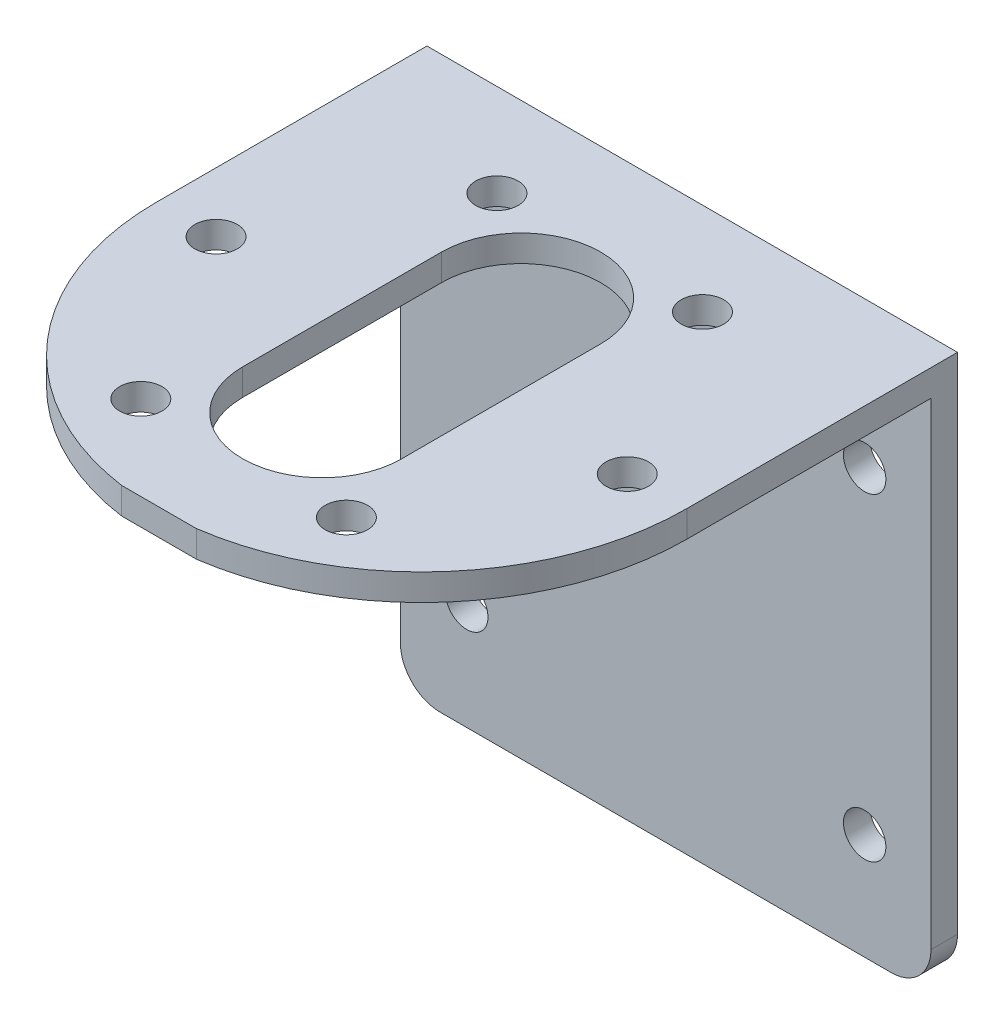
SolidWorks part; units mm, degrees
ref_plane "前视基准面" through (0, 0, 0) normal (0, 0, 1) x (1, 0, 0)
ref_plane "上视基准面" through (0, 0, 0) normal (0, 1, 0) x (1, 0, 0)
ref_plane "右视基准面" through (0, 0, 0) normal (1, 0, 0) x (0, 0, -1)
other "Configuration Table"
sketch "草图2" plane through (0, 0, 0) normal (0, 0, 1) x (1, 0, 0)
  line L0 (-14.6137, -6.4501) -> (-14.6137, 17.5499) construction
  line L1 (-19.6137, 26.5499) -> (20.3863, 26.5499)
  line L2 (-19.6137, 26.5499) -> (-19.6137, -14.4501)
  line L3 (-19.6137, -14.4501) -> (20.3863, -14.4501)
  line L4 (20.3863, 26.5499) -> (20.3863, -14.4501)
  line L5 (15.3863, -6.4501) -> (15.3863, 17.5499) construction
  line L6 (-14.6137, -6.4501) -> (15.3863, -6.4501) construction
  line L7 (15.3863, 17.5499) -> (-14.6137, 17.5499) construction
  circle A0 centre (-14.6137, -6.4501) radius 1.6
  circle A1 centre (15.3863, -6.4501) radius 1.6
  circle A2 centre (-14.6137, 17.5499) radius 1.6
  circle A3 centre (15.3863, 17.5499) radius 1.6
  point P12 (0.3863, -6.4501)
  point P13 (0.3863, -14.4501)
  dimension "D3" = 3.2
  dimension "D1" = 40
  dimension "D2" = 41
  dimension "D4" = 8
  dimension "D5" = 24
  dimension "D6" = 30
extrude "凸台-拉伸1" add sketch "草图2" along normal blind 40.2
sketch "草图3" plane through (0, 0, 40.2) normal (0, 0, 1) x (1, 0, 0)
  line L0 (20.3863, -14.4501) -> (20.3863, 26.5499) construction
  line L1 (-19.6137, 24.5499) -> (20.3863, 24.5499)
  line L2 (-19.6137, 24.5499) -> (-19.6137, -14.4501)
  line L3 (-19.6137, -14.4501) -> (20.3863, -14.4501)
  line L4 (20.3863, 24.5499) -> (20.3863, -14.4501)
  line L5 (-19.6137, 26.5499) -> (-19.6137, -14.4501) construction
  line L6 (-19.6137, -14.4501) -> (20.3863, -14.4501) construction
  line L7 (20.3863, 26.5499) -> (-19.6137, 26.5499) construction
  dimension "D1" = 2
extrude "切除-拉伸1" cut sketch "草图3" against normal blind 38.2
sketch "草图4" plane through (0, 24.5499, 0) normal (0, -1, 0) x (1, 0, 0)
  line L0 (-19.6137, 0) -> (20.3863, 0) construction
  line L1 (20.3863, 2) -> (-19.6137, 2) construction
  line L2 (-19.6137, 2) -> (-19.6137, 40.2) construction
  line L3 (-19.6137, 40.2) -> (20.3863, 40.2)
  line L4 (-19.6137, 40.2) -> (-19.6137, 20.4)
  line L6 (20.3863, 40.2) -> (20.3863, 20.4)
  line L7 (20.3863, 40.2) -> (-19.6137, 40.2) construction
  line L8 (20.3863, 2) -> (20.3863, 40.2) construction
  arc A0 (20.3863, 20.4) -> (-19.6137, 20.4) centre (0.3863, 20.4) ccw
  point P7 (0.3863, 2)
  line M2 (20.3863, 40.2) -> (-19.6137, 40.2)
  line M3 (-19.6137, 40.2) -> (-19.6137, 2)
  line M5 (20.3863, 2) -> (20.3863, 40.2)
  dimension "D1" = 20.4
  dimension "D2" = 40
extrude "切除-拉伸2" cut sketch "草图4" against normal through all contours A0 L3 M3 | A0 M5 M2
sketch "草图5" plane through (0, 24.5499, 0) normal (0, -1, 0) x (1, 0, 0)
  line L0 (-15.1137, 20.4) -> (0.3863, 20.4) construction
  line L1 (0.3863, 20.4) -> (15.8863, 20.4) construction
  line L2 (-7.3637, 33.8234) -> (0.3863, 20.4) construction
  line L3 (0.3863, 20.4) -> (8.1363, 6.9766) construction
  line L4 (8.1363, 33.8234) -> (0.3863, 20.4) construction
  line L5 (0.3863, 20.4) -> (-7.3637, 6.9766) construction
  line L6 (0.3863, 12.9) -> (0.3863, 27.9) construction
  line L7 (-5.6137, 12.9) -> (-5.6137, 27.9)
  line L8 (6.3863, 12.9) -> (6.3863, 27.9)
  line L10 (0.3863, 2.1) -> (0.3863, 2) construction
  line L11 (-19.6137, 2) -> (20.3863, 2) construction
  circle A0 centre (0.3863, 20.4) radius 15.5 construction
  circle A1 centre (-15.1137, 20.4) radius 1.6
  circle A2 centre (15.8863, 20.4) radius 1.6
  circle A3 centre (-7.3637, 33.8234) radius 1.6
  circle A4 centre (8.1363, 33.8234) radius 1.6
  circle A5 centre (-7.3637, 6.9766) radius 1.6
  circle A6 centre (8.1363, 6.9766) radius 1.6
  arc A7 (-5.6137, 12.9) -> (6.3863, 12.9) centre (0.3863, 12.9) ccw
  arc A8 (6.3863, 27.9) -> (-5.6137, 27.9) centre (0.3863, 27.9) ccw
  circle A9 centre (0.3863, 20.4) radius 18.3 construction
  point P17 (0.3863, 20.4)
  dimension "D1" = 31
  dimension "D2" = 3.2
  dimension "D5" = 15
  dimension "D7" = 36.6
  dimension "D8" = 0.1
  dimension "D9" = 6
  dimension "D3" = 60
  dimension "D4" = 60
  dimension "D6" = 12
extrude "切除-拉伸3" cut sketch "草图5" against normal through all
fillet "圆角1" radius 3 2 edges at (20.3863, -14.4501, 1) (-19.6137, -14.4501, 1)
sketch "草图6" plane through (0, 24.5499, 0) normal (0, -1, 0) x (1, 0, 0)
  line L0 (0.3863, 6.9) -> (0.3863, 2)
  line L1 (-16.6137, 2) -> (17.3863, 2) construction
  arc A0 (-5.6137, 12.9) -> (6.3863, 12.9) centre (0.3863, 12.9) ccw construction
